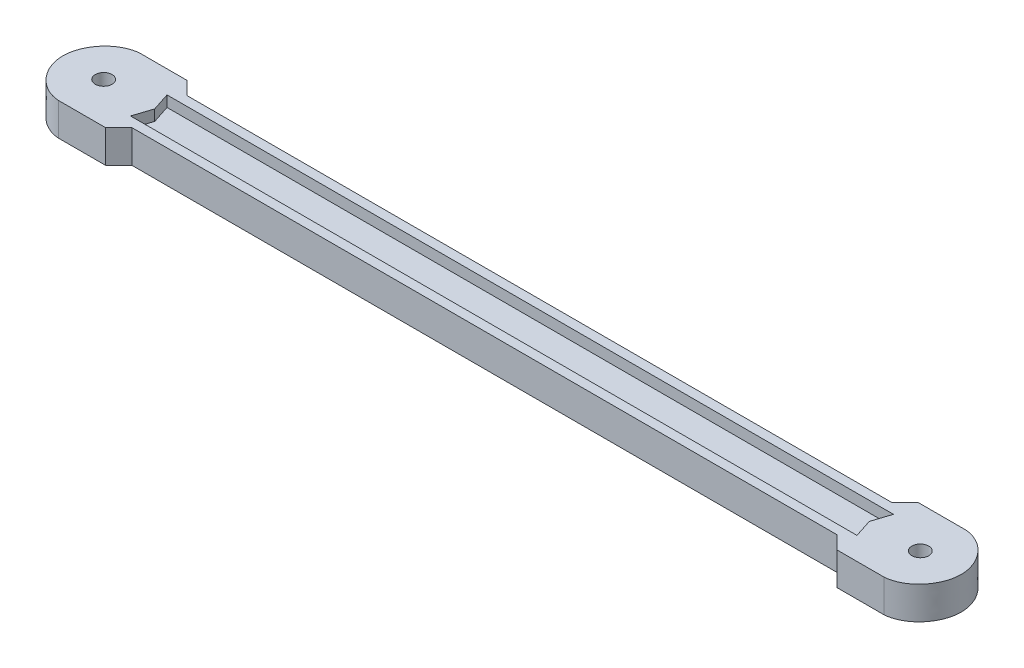
SolidWorks part; units mm, degrees
ref_plane "Plan de face" through (0, 0, 0) normal (0, 0, 1) x (1, 0, 0)
ref_plane "Plan de dessus" through (0, 0, 0) normal (0, 1, 0) x (1, 0, 0)
ref_plane "Plan de droite" through (0, 0, 0) normal (1, 0, 0) x (0, 0, -1)
sketch "Esquisse1" plane through (0, 0, 0) normal (0, 1, 0) x (1, 0, 0)
  line L0 (-82.5, -7.5) -> (-82.5, 7.5)
  line L1 (-3.3, 0) -> (3.3, 0) construction
  line L2 (-82.5, 7.5) -> (82.5, 7.5)
  line L3 (0, -3.3) -> (0, 3.3) construction
  line L4 (-82.5, -7.5) -> (82.5, -7.5)
  line L5 (82.5, -7.5) -> (82.5, 7.5)
  point P5 (-82.5, 0)
  point P6 (82.5, 0)
  point P10 (0, -7.5)
  point P11 (0, 7.5)
  dimension "D1" = 15
  dimension "D2" = 165
extrude "Boss.-Extru.1" add sketch "Esquisse1" along normal blind 6
sketch "Esquisse2" plane through (0, 0, 0) normal (0, -1, 0) x (1, 0, 0)
  line L0 (3.3, 0) -> (-3.3, 0) construction
  line L1 (0, -3.3) -> (0, 3.3) construction
  line L2 (-82.5, -7.5) -> (-82.5, 7.5) construction
  circle A0 centre (-75, 0) radius 7.5 construction
  circle A1 centre (75, 0) radius 7.5 construction
  dimension "D1" = 7.5
  dimension "D2" = 15
sketch "Esquisse3" plane through (0, 0, 0) normal (0, -1, 0) x (1, 0, 0)
  line L0 (-82.5, -7.5) -> (-82.5, 7.5) construction
  line L1 (0, -3.3) -> (0, 3.3) construction
  circle A0 centre (-75, 0) radius 1.55
  circle A1 centre (75, 0) radius 1.55
  dimension "D1" = 3.1
  dimension "D2" = 7.5
sketch "Esquisse4" plane through (0, 6, 0) normal (0, 1, 0) x (1, 0, 0)
  line L0 (-67.1592, 7.5) -> (-64.7385, 5.0794)
  line L1 (82.5, 7.5) -> (-82.5, 7.5) construction
  line L2 (-64.7385, 5.0794) -> (64.7385, 5.0794)
  line L3 (0, -3.3) -> (0, 3.3) construction
  line L4 (-67.1592, 7.5) -> (-75, 7.5)
  line L5 (-3.3, 0) -> (3.3, 0) construction
  line L6 (-82.5, 7.5) -> (-82.5, -7.5) construction
  line L7 (67.1592, 7.5) -> (75, 7.5)
  line L8 (67.1592, 7.5) -> (64.7385, 5.0794)
  line L9 (67.1592, -7.5) -> (64.7385, -5.0794)
  line L10 (67.1592, -7.5) -> (75, -7.5)
  line L11 (-67.1592, -7.5) -> (-75, -7.5)
  line L12 (-64.7385, -5.0794) -> (64.7385, -5.0794)
  line L13 (-67.1592, -7.5) -> (-64.7385, -5.0794)
  line L15 (-90.3206, 15) -> (90.3206, 15)
  line L16 (-90.3206, 15) -> (-90.3206, -15)
  line L17 (-90.3206, -15) -> (90.3206, -15)
  line L18 (90.3206, 15) -> (90.3206, -15)
  line L19 (-90.3206, 15) -> (90.3206, -15) construction
  line L20 (-90.3206, -15) -> (90.3206, 15) construction
  circle A0 centre (-75, 0) radius 7.5 construction
  spline S0 degree 3 poles (-75, 7.5) (-79.0852, 7.774) (-85.9148, 0) (-79.0852, -7.774) (-75, -7.5) knots 0 0 0 0 0.5 1 1 1 1
  spline S1 degree 3 poles (75, 7.5) (79.0852, 7.774) (85.9148, 0) (79.0852, -7.774) (75, -7.5) knots 0 0 0 0 0.5 1 1 1 1
  point P28 (0, 5.0794)
  point P42 (0, -5.0794)
  point P43 (0, 0)
  dimension "D1" = 17.7615
  dimension "D4" = 15.3206
  dimension "D2" = 15.3408
  dimension "D3" = 15.3206
  dimension "D5" = 30
  dimension "D6" = 7.5
  dimension "D7" = 7.5
  dimension "D8" = 7.5
  dimension "D9" = 7.5
  dimension "D10" = 7.5
  dimension "D11" = 1.9098
  dimension "D12" = 2.5
extrude "Enlèv. mat.-Extru.1" cut sketch "Esquisse4" against normal blind 12
extrude "Enlèv. mat.-Extru.2" cut sketch "Esquisse3" against normal blind 12
sketch "Esquisse5" plane through (0, 6, 0) normal (0, 1, 0) x (1, 0, 0)
  line L0 (-65.625, 0) -> (-66.7174, 3.3519)
  line L1 (-3.3, 0) -> (3.3, 0) construction
  line L2 (-66.7174, 3.3519) -> (66.7174, 3.3519)
  line L3 (0, -3.3) -> (0, 3.3) construction
  line L4 (-66.7174, -3.3519) -> (66.7174, -3.3519)
  line L5 (-65.625, 0) -> (-66.7174, -3.3519)
  line L6 (65.625, 0) -> (66.7174, -3.3519)
  line L7 (65.625, 0) -> (66.7174, 3.3519)
  line L8 (-64.7385, 5.0794) -> (64.7385, 5.0794) construction
  point P12 (0, -3.3519)
  point P13 (0, 3.3519)
  dimension "D1" = 8.2826
  dimension "D2" = 1.9789
  dimension "D3" = 9.375
  dimension "D4" = 1.7274
extrude "Enlèv. mat.-Extru.3" cut sketch "Esquisse5" against normal blind 2
